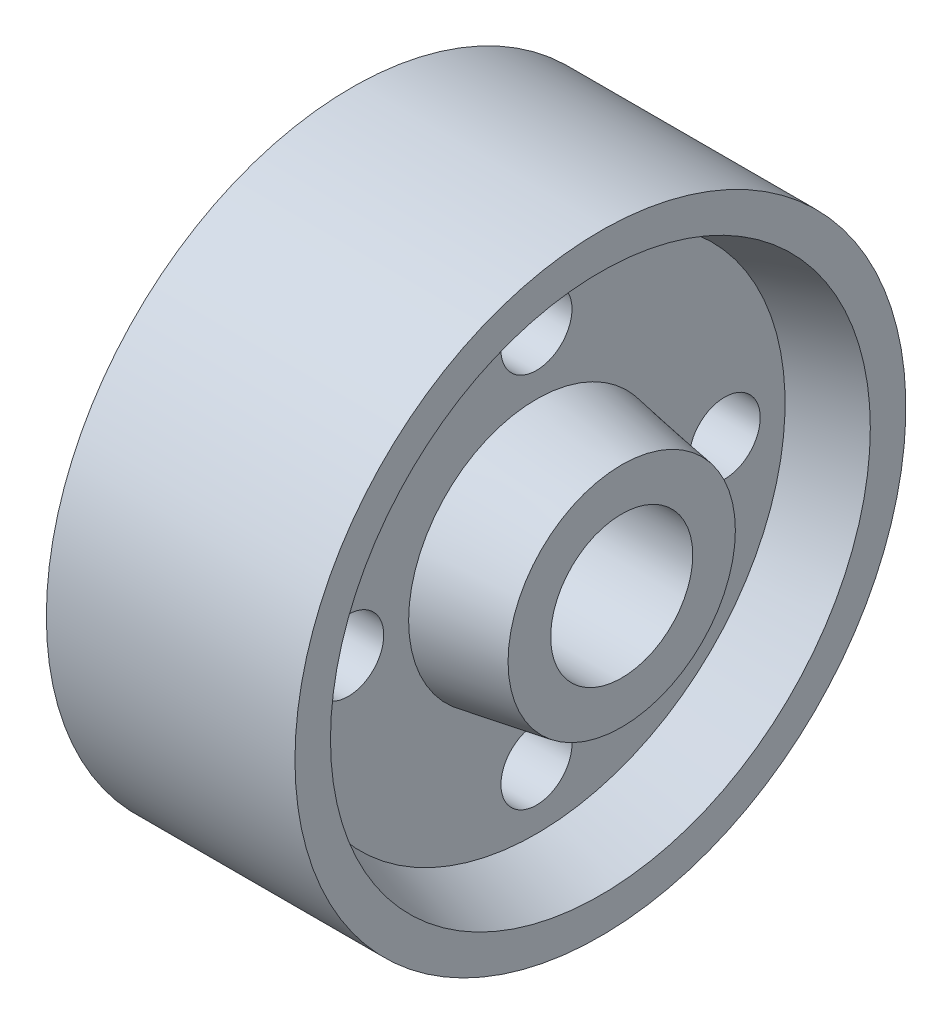
SolidWorks part; units mm, degrees
ref_plane "Front Plane" through (0, 0, 0) normal (0, 0, 1) x (1, 0, 0)
ref_plane "Top Plane" through (0, 0, 0) normal (0, 1, 0) x (1, 0, 0)
ref_plane "Right Plane" through (0, 0, 0) normal (1, 0, 0) x (0, 0, -1)
sketch "Sketch1" plane through (0, 0, 0) normal (0, 1, 0) x (1, 0, 0)
  line L0 (0, 0) -> (51.5115, 0) construction
  line L1 (0, 0) -> (0, 16)
  line L2 (0, 16) -> (12, 18)
  line L3 (12, 18) -> (12, 35)
  line L4 (12, 35) -> (3, 38)
  line L5 (3, 38) -> (3, 43)
  line L6 (3, 43) -> (38, 43)
  line L7 (20.5, 43) -> (20.5, 0) construction
  line L8 (41, 0) -> (41, 16)
  line L9 (41, 16) -> (29, 18)
  line L10 (29, 18) -> (29, 35)
  line L11 (29, 35) -> (38, 38)
  line L12 (38, 38) -> (38, 43)
  line L13 (0, 0) -> (41, 0) construction
  line L14 (0, 0) -> (41, 0)
  point P17 (42.8758, 0)
  point P18 (51.5115, 0)
  dimension "D1" = 32
  dimension "D2" = 36
  dimension "D3" = 70
  dimension "D4" = 76
  dimension "D5" = 86
  dimension "D6" = 12
  dimension "D7" = 20.5
  dimension "D8" = 17.5
revolve "Revolve1" add sketch "Sketch1" angle 360 about L14
sketch "Sketch2" plane through (41, 0, 0) normal (1, 0, 0) x (0, 0, -1)
  line L0 (0, 0) -> (0, 26.5) construction
  circle A0 centre (0, 0) radius 26.5 construction
  circle A1 centre (0, 26.5) radius 5
  circle A2 centre (26.5, 0) radius 5
  circle A3 centre (0, -26.5) radius 5
  circle A4 centre (-26.5, 0) radius 5
  point P5 (-30.0048, -1.5435)
  point P6 (0, 0)
  point P14 (0, 0)
  dimension "D1" = 53
  dimension "D2" = 10
  dimension "D3" = 4
extrude "Cut-Extrude1" cut sketch "Sketch2" against normal through all
sketch "Sketch3" plane through (41, 0, 0) normal (1, 0, 0) x (0, 0, -1)
  circle A0 centre (0, 0) radius 10
  dimension "D1" = 20
extrude "Cut-Extrude2" cut sketch "Sketch3" against normal through all
